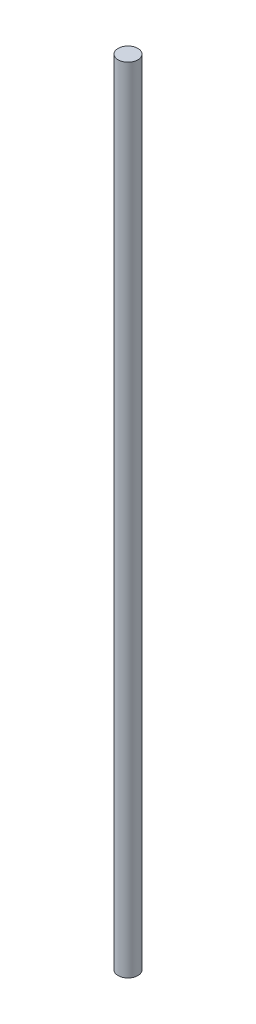
SolidWorks part; units mm, degrees
material "3003 Alloy"
ref_plane "Front Plane" through (0, 0, 0) normal (0, 0, 1) x (1, 0, 0)
ref_plane "Top Plane" through (0, 0, 0) normal (0, 1, 0) x (1, 0, 0)
ref_plane "Right Plane" through (0, 0, 0) normal (1, 0, 0) x (0, 0, -1)
sketch "Sketch1" plane through (0, 0, 0) normal (0, 1, 0) x (1, 0, 0)
  circle A0 centre (0, 0) radius 0.25
  dimension "D1" = 0.5
extrude "Boss-Extrude1" add sketch "Sketch1" along normal mid plane 20
